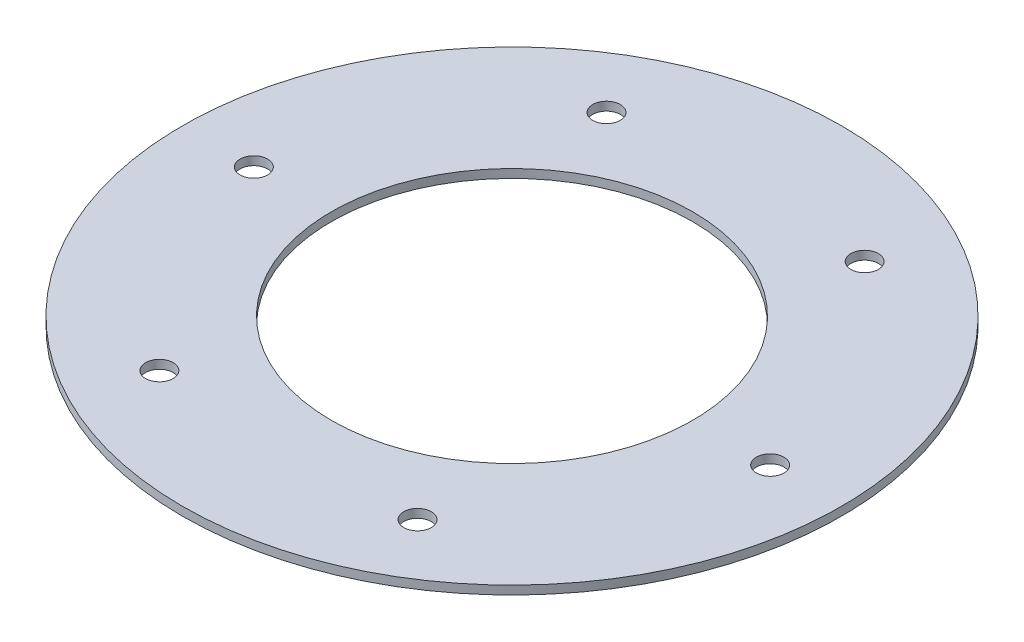
SolidWorks part; units mm, degrees
material "Balsa"
ref_plane "Front Plane" through (0, 0, 0) normal (0, 0, 1) x (1, 0, 0)
ref_plane "Top Plane" through (0, 0, 0) normal (0, 1, 0) x (1, 0, 0)
ref_plane "Right Plane" through (0, 0, 0) normal (1, 0, 0) x (0, 0, -1)
sketch "Sketch1" plane through (0, 0, 0) normal (0, 1, 0) x (1, 0, 0)
  line L0 (-38.3, 0) -> (38.3, 0) construction
  line L1 (0, 38.3) -> (0, -38.3) construction
  circle A0 centre (0, 0) radius 38.3
  circle A1 centre (30, 0) radius 1.6
  circle A2 centre (0, 0) radius 21
  circle A3 centre (15, -25.9808) radius 1.6
  circle A4 centre (-15, -25.9808) radius 1.6
  circle A5 centre (-30, 0) radius 1.6
  circle A6 centre (-15, 25.9808) radius 1.6
  circle A7 centre (15, 25.9808) radius 1.6
  point P23 (0, 0)
  dimension "D1" = 42
  dimension "D2" = 76.6
  dimension "D3" = 3.2
  dimension "D4" = 30
  dimension "D5" = 6
extrude "Boss-Extrude1" add sketch "Sketch1" along normal blind 1
